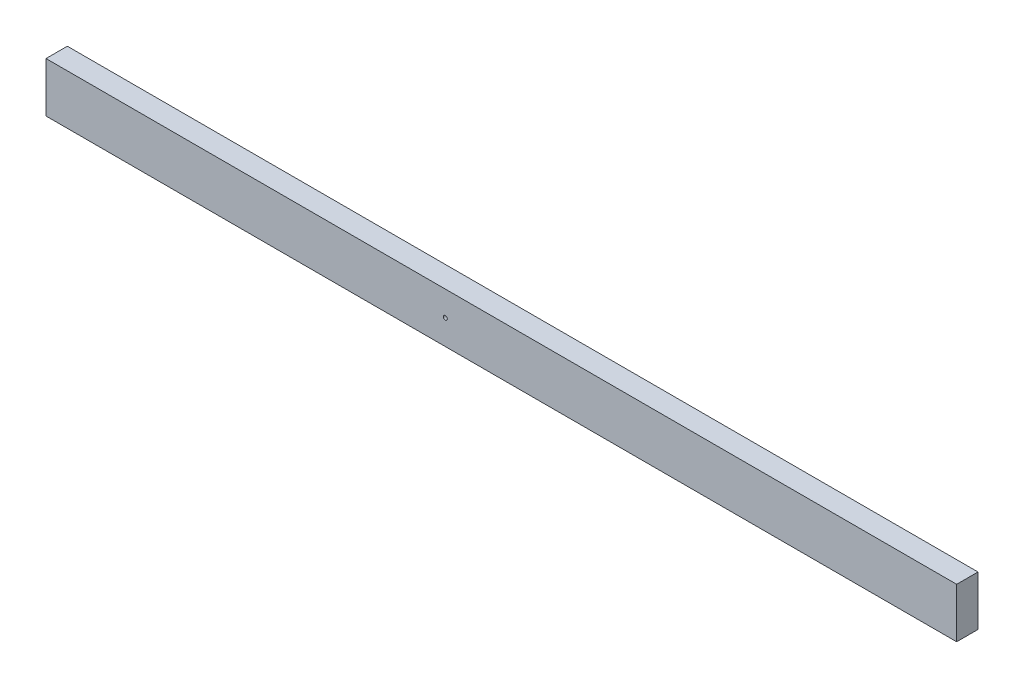
SolidWorks part; units mm, degrees
material "Pine"
ref_plane "Front Plane" through (0, 0, 0) normal (0, 0, 1) x (1, 0, 0)
ref_plane "Top Plane" through (0, 0, 0) normal (0, 1, 0) x (1, 0, 0)
ref_plane "Right Plane" through (0, 0, 0) normal (1, 0, 0) x (0, 0, -1)
sketch "Sketch1" plane through (0, 0, 0) normal (1, 0, 0) x (0, 0, -1)
  line L1 (-19.05, -44.45) -> (19.05, -44.45)
  line L2 (-19.05, -44.45) -> (-19.05, 44.45)
  line L3 (-19.05, 44.45) -> (19.05, 44.45)
  line L4 (19.05, -44.45) -> (19.05, 44.45)
  line L5 (-19.05, -44.45) -> (19.05, 44.45) construction
  line L6 (-19.05, 44.45) -> (19.05, -44.45) construction
  point P0 (0, 0)
  dimension "D1" = 88.9
  dimension "D2" = 38.1
extrude "Boss-Extrude1" add sketch "Sketch1" along normal blind 1625.6
hole_wizard "9/32 (0.28125) Diameter Hole1" positions "Sketch3" profile "Sketch2" hole size "9/32" standard "ANSI Inch" end condition through all
sketch "Sketch3" plane through (0, 0, 19.05) normal (0, 0, 1) x (1, 0, 0)
  line L1 (1625.6, -44.45) -> (0, -44.45) construction
  line L2 (1625.6, 44.45) -> (1625.6, -44.45) construction
  point P0 (712.7875, 0)
  dimension "D1" = 912.8125
  dimension "D2" = 44.45
sketch "Sketch2" plane through (712.7875, 0, 19.05) normal (1, 0, 0) x (0, -1, 0)
  line L0 (0, 0) -> (0, 38.1)
  line L1 (0, 38.1) -> (3.5719, 38.1)
  line L2 (3.5719, 38.1) -> (3.5719, 0)
  line L5 (3.5719, 0) -> (0, 0)
  line L11 (0, -6.35) -> (0, 107.95) construction
  dimension "Thru Hole Dia." = 7.1437
  dimension "Thru Hole Depth" = 38.1
